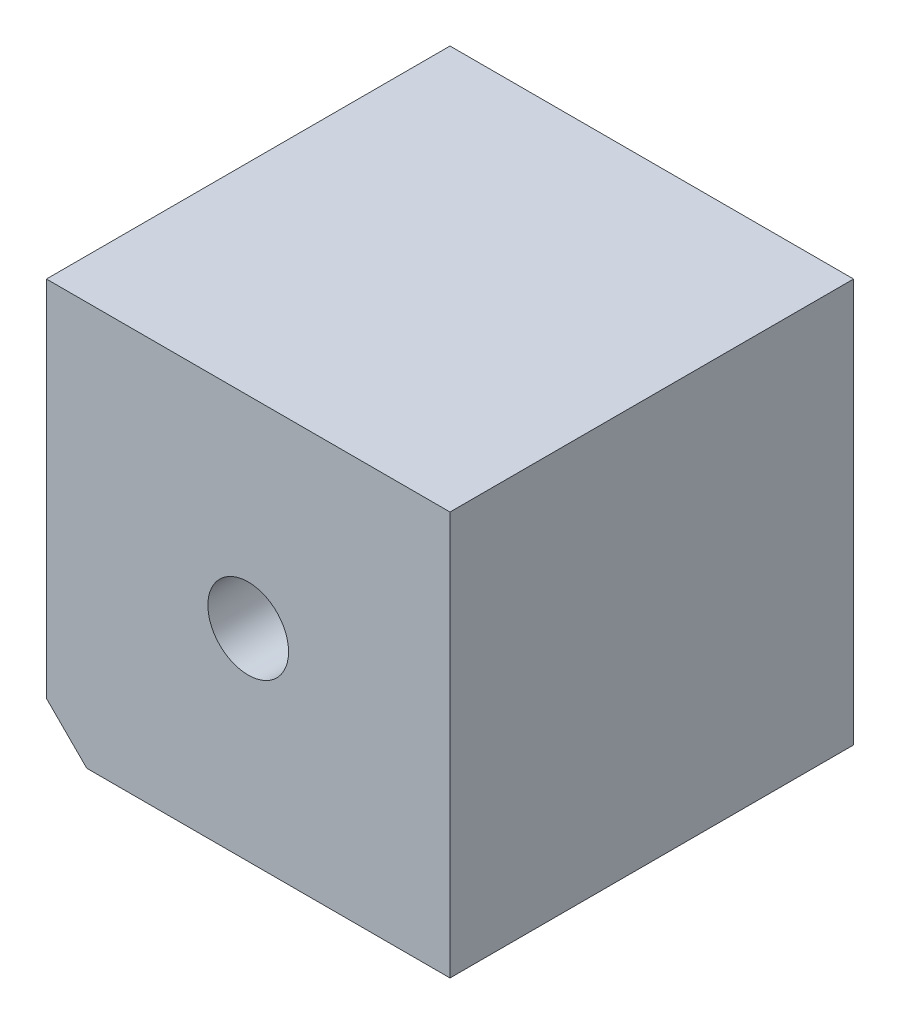
SolidWorks part; units mm, degrees
ref_plane "Front Plane" through (0, 0, 0) normal (0, 0, 1) x (1, 0, 0)
ref_plane "Top Plane" through (0, 0, 0) normal (0, 1, 0) x (1, 0, 0)
ref_plane "Right Plane" through (0, 0, 0) normal (1, 0, 0) x (0, 0, -1)
sketch "Sketch1" plane through (0, 0, 0) normal (0, 0, 1) x (1, 0, 0)
  line L1 (-50, 50) -> (50, 50)
  line L2 (-50, 50) -> (-50, -50)
  line L3 (-50, -50) -> (50, -50)
  line L4 (50, 50) -> (50, -50)
  line L5 (-50, 50) -> (50, -50) construction
  line L6 (-50, -50) -> (50, 50) construction
  point P0 (0, 0)
  dimension "D1" = 100
extrude "Boss-Extrude1" add sketch "Sketch1" along normal blind 100
sketch "Sketch2" plane through (0, 0, 100) normal (0, 0, 1) x (1, 0, 0)
  circle A0 centre (0, 0) radius 10
  point P2 (0, 0)
  dimension "D1" = 20
extrude "Cut-Extrude1" cut sketch "Sketch2" against normal blind 58
chamfer "Chamfer1" distance 10 angle 45 1 edges at (-50, -50, 50)
